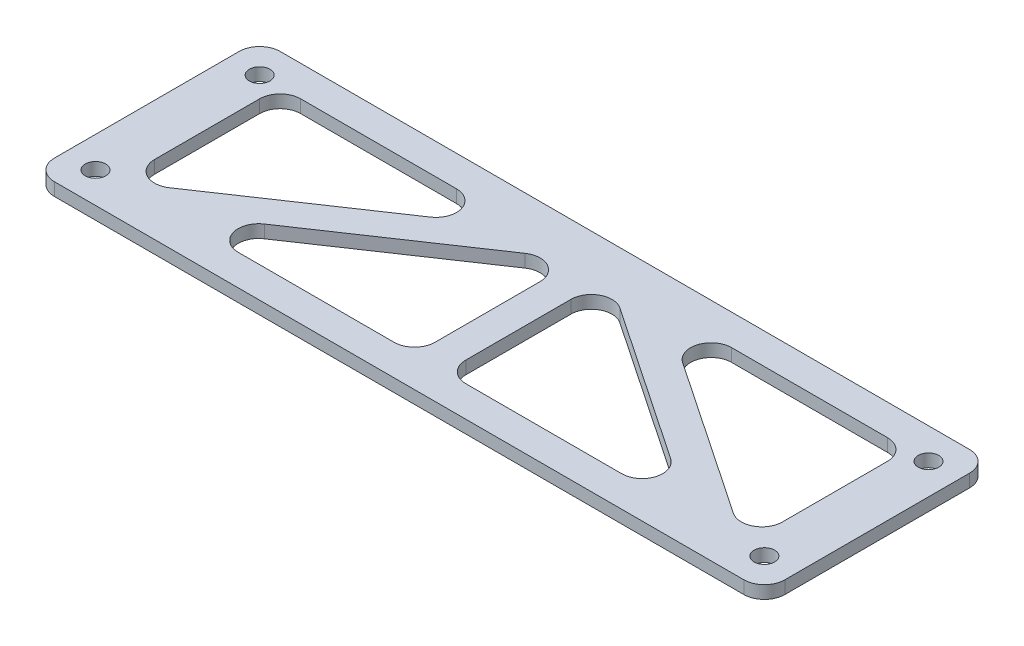
SolidWorks part; units mm, degrees
ref_plane "Front Plane" through (0, 0, 0) normal (0, 0, 1) x (1, 0, 0)
ref_plane "Top Plane" through (0, 0, 0) normal (0, 1, 0) x (1, 0, 0)
ref_plane "Right Plane" through (0, 0, 0) normal (1, 0, 0) x (0, 0, -1)
sketch "Sketch1" plane through (0, 0, 0) normal (0, 1, 0) x (1, 0, 0)
  line L0 (-61.1998, 16) -> (-61.1998, -16)
  line L1 (65.1998, -16) -> (-65.1998, -16) construction
  line L2 (65.1998, -16) -> (65.1998, 16) construction
  line L3 (65.1998, 16) -> (-65.1998, 16) construction
  line L4 (-65.1998, -16) -> (-65.1998, 16) construction
  line L5 (0, 16) -> (0, -16) construction
  line L6 (65.1998, 0) -> (-65.1998, 0) construction
  line L7 (71.1998, -22) -> (-71.1998, -22)
  line L8 (71.1998, -22) -> (71.1998, 22)
  line L9 (71.1998, 22) -> (-71.1998, 22)
  line L10 (-71.1998, -22) -> (-71.1998, 22)
  line L11 (0, 22) -> (0, -22) construction
  line L12 (71.1998, 0) -> (-71.1998, 0) construction
  line L13 (-61.1998, -16) -> (-13.7335, 16)
  line L14 (-13.7335, 16) -> (-61.1998, 16)
  line L15 (-3, 16) -> (-50.4662, -16)
  line L16 (-50.4662, -16) -> (-3, -16)
  line L17 (-3, -16) -> (-3, 16)
  line L18 (3, 16) -> (3, -16)
  line L19 (3, -16) -> (50.4662, -16)
  line L20 (50.4662, -16) -> (3, 16)
  line L21 (61.1998, -16) -> (13.7335, 16)
  line L22 (13.7335, 16) -> (61.1998, 16)
  line L23 (61.1998, 16) -> (61.1998, -16)
  circle A0 centre (-65.1998, 16) radius 2
  circle A1 centre (65.1998, 16) radius 2
  circle A2 centre (65.1998, -16) radius 2
  circle A3 centre (-65.1998, -16) radius 2
  point P0 (0, 0)
  point P8 (0, 0)
  dimension "D3" = 4
  dimension "D4" = 4
  dimension "D5" = 4
  dimension "D6" = 4
  dimension "D1" = 130.3995
  dimension "D2" = 32
  dimension "D7" = 6
  dimension "D8" = 6
  dimension "D9" = 4
  dimension "D10" = 4
  dimension "D11" = 3
  dimension "D12" = 3
  dimension "D13" = 6
  dimension "D14" = 6
extrude "Boss-Extrude1" add sketch "Sketch1" along normal blind 2.5
fillet "Fillet1" radius 4 16 edges at (-71.1998, 1.25, -22) (71.1998, 1.25, -22) (71.1998, 1.25, 22) (-71.1998, 1.25, 22) (50.4662, 1.25, 16) (61.1998, 1.25, 16) (-3, 1.25, 16) (3, 1.25, 16) (61.1998, 1.25, -16) (13.7335, 1.25, -16) (3, 1.25, -16) (-3, 1.25, -16) (-50.4662, 1.25, 16) (-13.7335, 1.25, -16) (-61.1998, 1.25, 16) (-61.1998, 1.25, -16)
